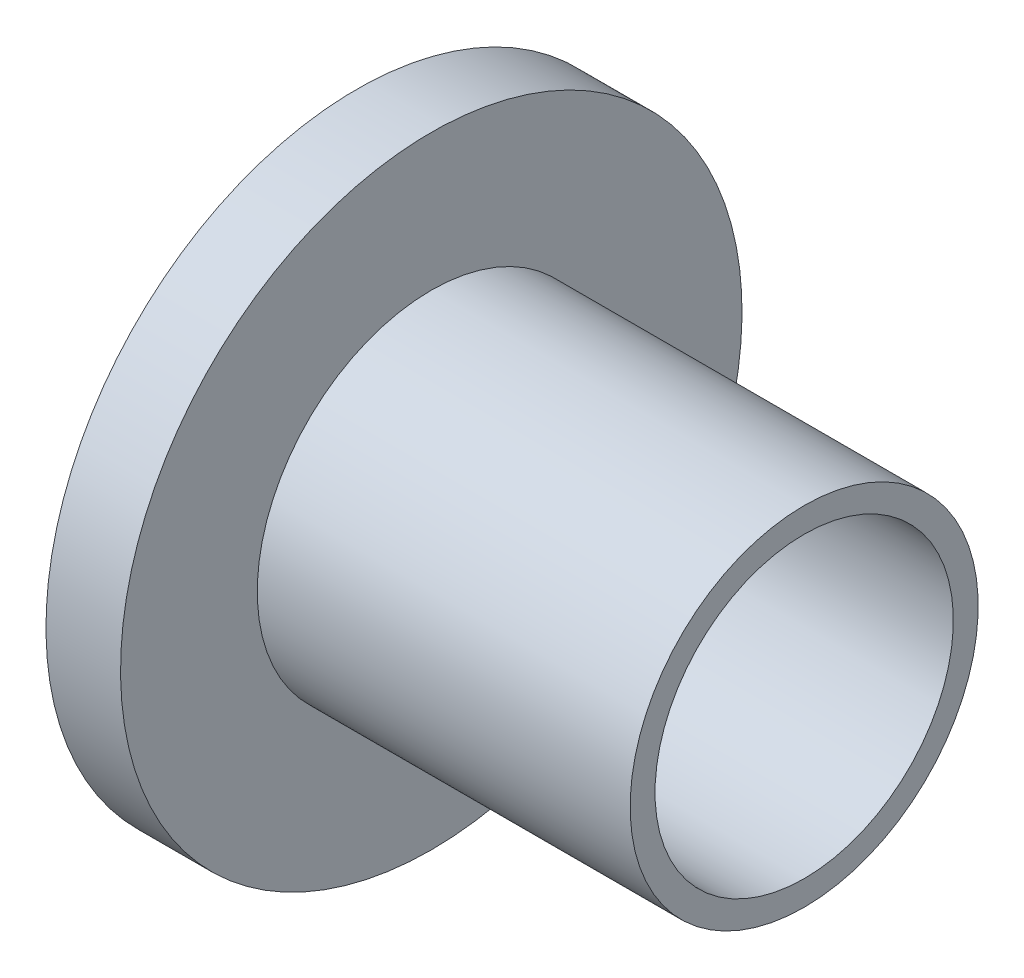
SolidWorks part; units mm, degrees
ref_plane "Front Plane" through (0, 0, 0) normal (0, 0, 1) x (1, 0, 0)
ref_plane "Top Plane" through (0, 0, 0) normal (0, 1, 0) x (1, 0, 0)
ref_plane "Right Plane" through (0, 0, 0) normal (1, 0, 0) x (0, 0, -1)
sketch "Sketch1" plane through (0, 0, 0) normal (0, 0, 1) x (1, 0, 0)
  line L0 (-64.9001, 0) -> (64.9001, 0) construction
  line L1 (-6, 25) -> (-6, 10)
  line L2 (-6, 10) -> (0, 10)
  line L3 (0, 10) -> (0, 12)
  line L4 (0, 12) -> (30, 12)
  line L5 (30, 12) -> (30, 14)
  line L6 (30, 14) -> (0, 14)
  line L7 (0, 14) -> (0, 25)
  line L8 (0, 25) -> (-6, 25)
  point P3 (0, 0)
  point P6 (-3, 25)
  dimension "D1" = 24
  dimension "D2" = 28
  dimension "D3" = 20
  dimension "D4" = 50
  dimension "D5" = 6
  dimension "D6" = 30
revolve "Revolve1" add sketch "Sketch1" angle 360 about L0
